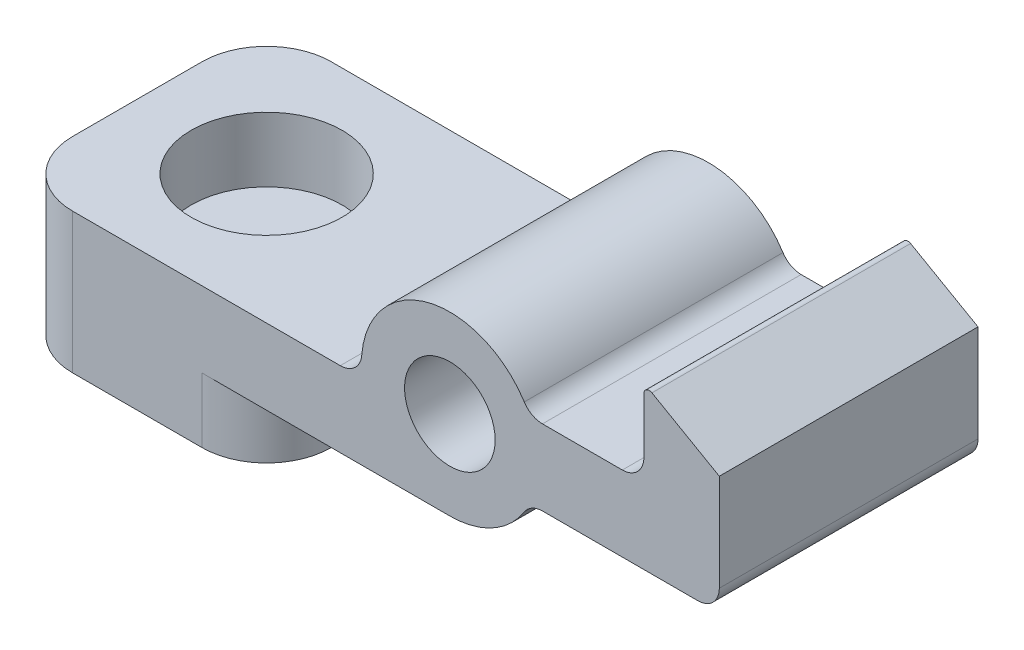
SolidWorks part; units mm, degrees
ref_plane "Front Plane" through (0, 0, 0) normal (0, 0, 1) x (1, 0, 0)
ref_plane "Top Plane" through (0, 0, 0) normal (0, 1, 0) x (1, 0, 0)
ref_plane "Right Plane" through (0, 0, 0) normal (1, 0, 0) x (0, 0, -1)
sketch "Sketch1" plane through (0, 0, 0) normal (0, 0, 1) x (1, 0, 0)
  line L0 (0, 0) -> (12.5, 0) construction
  line L1 (12.5, 5.75) -> (12.5, -1.75)
  line L2 (12.5, -1.75) -> (3.7078, -1.75)
  line L3 (12.5, 5.75) -> (9, 5.75)
  line L4 (9, 5.75) -> (9, 1.75)
  line L5 (9, 1.75) -> (3.7078, 1.75)
  line L6 (9, 1.75) -> (9, -1.75) construction
  line L7 (0, -4.1) -> (-20.5, -4.1)
  line L8 (-20.5, -4.1) -> (-20.5, -0.6)
  line L9 (-20.5, -0.6) -> (-4.0559, -0.6)
  circle A0 centre (0, 0) radius 2.1
  arc A1 (0, -4.1) -> (3.7078, -1.75) centre (0, 0) ccw
  arc A2 (3.7078, 1.75) -> (-4.0559, -0.6) centre (0, 0) ccw
  point P7 (9, 0)
  dimension "D1" = 4.2
  dimension "D2" = 2
  dimension "D3" = 12.5
  dimension "D4" = 3.5
  dimension "D5" = 7.5
  dimension "D6" = 3.5
  dimension "D7" = 3.5
  dimension "D8" = 33
extrude "Boss-Extrude1" add sketch "Sketch1" along normal blind 12 contours A0 | L9 A2 L5 L4 L3 L1 L2 A1 L7 L8
fillet "Fillet1" radius 1 5 edges at (12.5, -1.75, 6) (3.7078, 1.75, 6) (3.7078, -1.75, 6) (-4.0559, -0.6, 6) (9, 1.75, 6)
sketch "Sketch3" plane through (0, 0, 12) normal (0, 0, 1) x (1, 0, 0)
  line L0 (9, 5.75) -> (12.5, 5.75)
  line L1 (12.5, 5.75) -> (12.5, 3.75)
  line L2 (12.5, 5.75) -> (12.5, -0.75) construction
  line L3 (12.5, 3.75) -> (9, 5.75)
  dimension "D1" = 2
extrude "Cut-Extrude1" cut sketch "Sketch3" against normal up to surface (12 mm away) up to face at (1.8576, 0.4054, 0)
fillet "Fillet3" radius 0.25 1 edges at (9, 5.75, 6)
fillet "Fillet4" radius 3 2 edges at (-20.5, -2.35, 12) (-20.5, -2.35, 0)
sketch "Sketch6" plane through (0, -4.1, 0) normal (0, -1, 0) x (1, 0, 0)
  line L0 (-8.5, 12) -> (-8.5, 0)
  line L4 (0, 12) -> (-17.5, 12)
  line L5 (-20.5, 9) -> (-20.5, 3)
  line L6 (-17.5, 0) -> (0, 0)
  line L7 (0, 0) -> (0, 12)
  line L8 (-8.5, 12) -> (-17.5, 12)
  line L9 (-20.5, 9) -> (-20.5, 3)
  line L10 (-17.5, 0) -> (-8.5, 0)
  arc A2 (-17.5, 12) -> (-20.5, 9) centre (-17.5, 9) ccw
  arc A3 (-20.5, 3) -> (-17.5, 0) centre (-17.5, 3) ccw
  arc A4 (-17.5, 12) -> (-20.5, 9) centre (-17.5, 9) ccw
  arc A5 (-20.5, 3) -> (-17.5, 0) centre (-17.5, 3) ccw
  dimension "D2" = 12
  dimension "D1" = 0
extrude "Boss-Extrude2" add sketch "Sketch6" along normal blind 3
fillet "Fillet5" radius 3 2 edges at (-8.5, -5.6, 0) (-8.5, -5.6, 12)
sketch "Sketch7" plane through (0, -0.6, 0) normal (0, 1, 0) x (1, 0, 0)
  line L0 (-20.5, -9) -> (-20.5, -3) construction
  circle A0 centre (-14.5, -6) radius 3.5
  point P2 (0, 0)
  point P5 (-20.5, -6)
  point P6 (-13.1737, -6)
  dimension "D1" = 7
  dimension "D2" = 6
extrude "Cut-Extrude4" cut sketch "Sketch7" against normal blind 3
